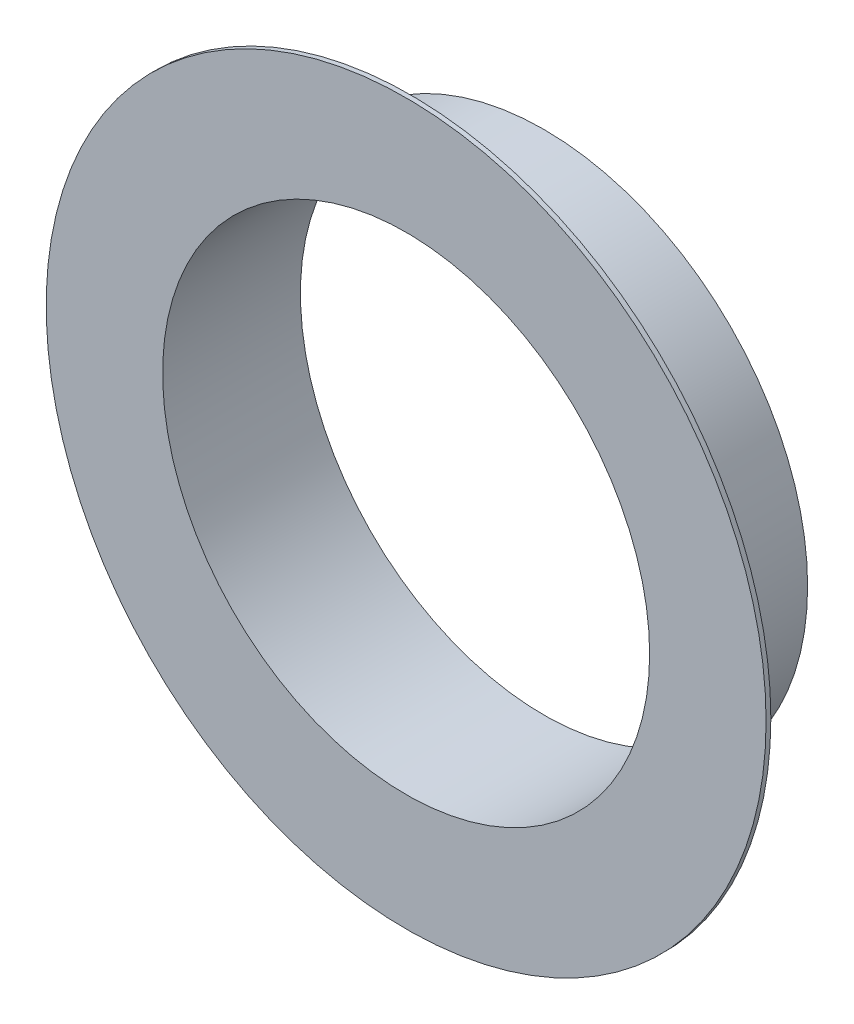
SolidWorks part; units mm, degrees
ref_plane "Front Plane" through (0, 0, 0) normal (0, 0, 1) x (1, 0, 0)
ref_plane "Top Plane" through (0, 0, 0) normal (0, 1, 0) x (1, 0, 0)
ref_plane "Right Plane" through (0, 0, 0) normal (1, 0, 0) x (0, 0, -1)
sketch "Sketch1" plane through (0, 0, 0) normal (0, 0, 1) x (1, 0, 0)
  circle A0 centre (0, 0) radius 102.5 construction
  circle A1 centre (0, 0) radius 102.5
  circle A2 centre (0, 0) radius 111 construction
  circle A3 centre (0, 0) radius 111
extrude "Boss-Extrude1" add sketch "Sketch1" along normal blind 56
sketch "Sketch2" plane through (0, 0, 56) normal (0, 0, 1) x (1, 0, 0)
  line L0 (0, 0) -> (29.4395, 102.2639) construction
  circle A0 centre (29.4395, 102.2639) radius 2.5447
extrude "Cut-Extrude1" cut sketch "Sketch2" against normal blind 15
pattern_circular "CirPattern1" count 8 over 360 about axis through (0, 0, 0) along (0, 0, 1) of "Cut-Extrude1"
sketch "Sketch3" plane through (0, 0, 56) normal (0, 0, 1) x (1, 0, 0)
  circle A0 centre (0, 0) radius 102.5 construction
  circle A1 centre (0, 0) radius 102.5
  circle A2 centre (0, 0) radius 151.5212
extrude "Boss-Extrude2" add sketch "Sketch3" along normal blind 2
